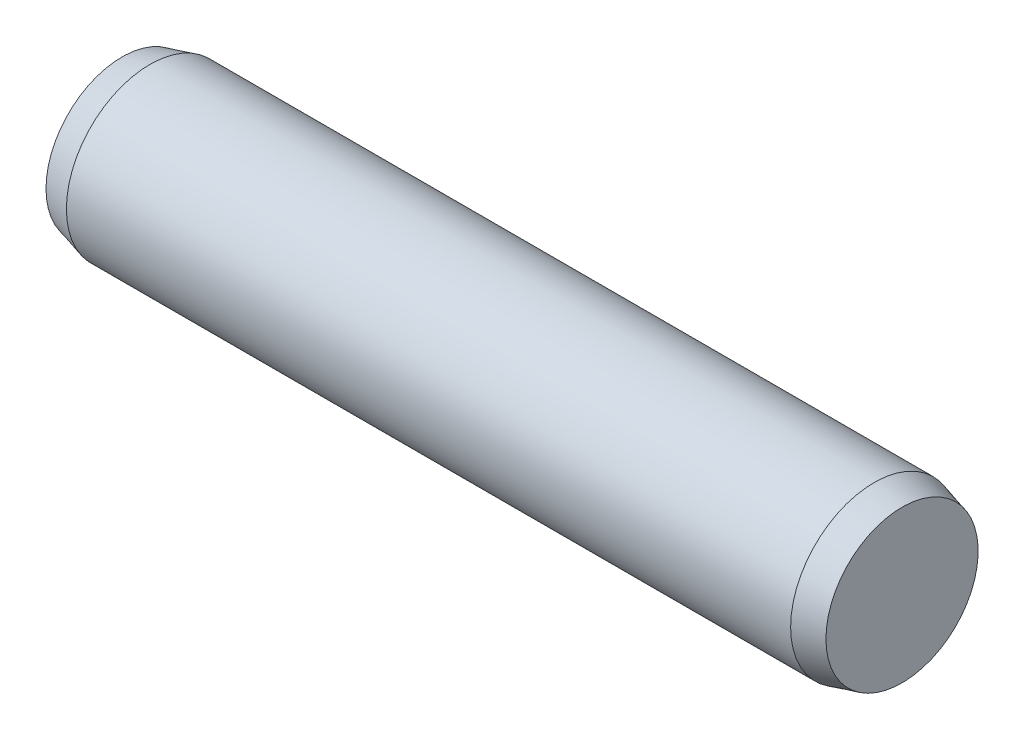
SolidWorks part; units mm, degrees
ref_plane "Front" through (0, 0, 0) normal (0, 0, 1) x (1, 0, 0)
ref_plane "Top" through (0, 0, 0) normal (0, 1, 0) x (1, 0, 0)
ref_plane "Right" through (0, 0, 0) normal (1, 0, 0) x (0, 0, -1)
sketch "Sketch1" plane through (0, 0, 0) normal (0, 0, 1) x (1, 0, 0)
  line L0 (0, 0) -> (14, 0)
  line L1 (14, 0) -> (14, 1.366)
  line L2 (14, 1.366) -> (13.5, 1.5)
  line L3 (13.5, 1.5) -> (0.5, 1.5)
  line L4 (0.5, 1.5) -> (0, 1.366)
  line L5 (0, 1.366) -> (0, 0)
  line L6 (-1.6557, 0) -> (2.6973, 0) construction
  dimension "l" = 14
  dimension "D2" = 15
  dimension "D3" = 15
  dimension "d" = 3
  dimension "c" = 0.5
  dimension "D6" = 0.5
revolve "Base-Revolve" add sketch "Sketch1" angle 360 about L6
equation "\"D6@Sketch1\" = \"c@Sketch1\""
